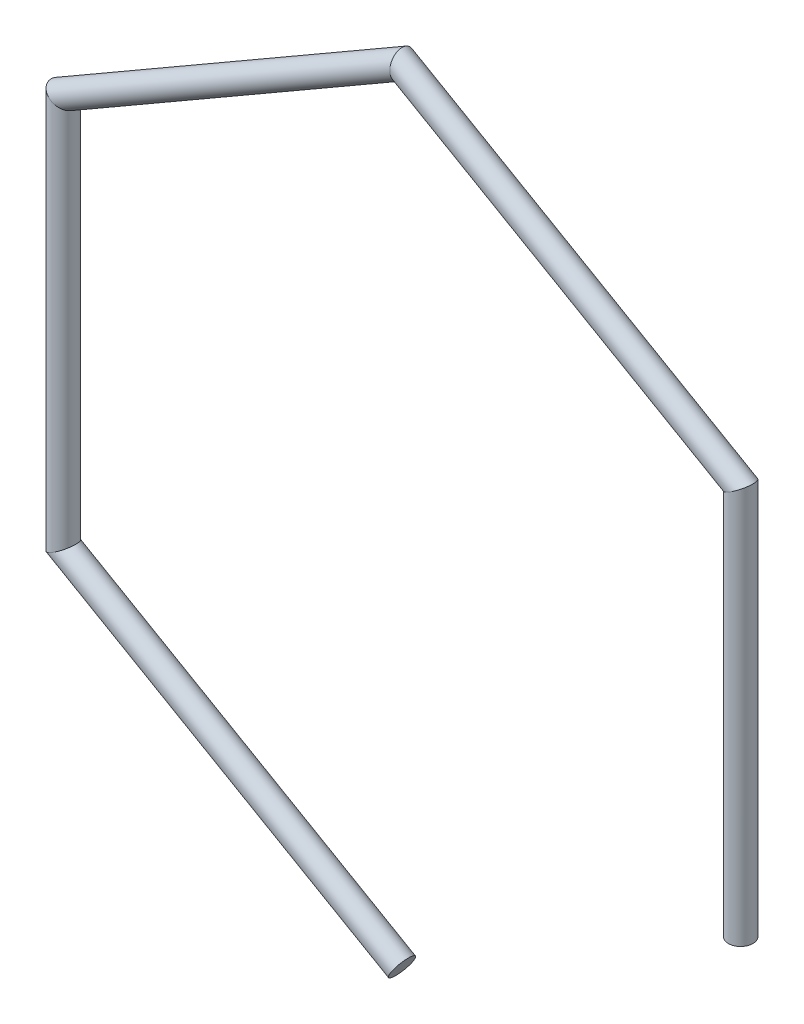
SolidWorks part; units mm, degrees
ref_plane "Front Plane" through (0, 0, 0) normal (0, 0, 1) x (1, 0, 0)
ref_plane "Top Plane" through (0, 0, 0) normal (0, 1, 0) x (1, 0, 0)
ref_plane "Right Plane" through (0, 0, 0) normal (1, 0, 0) x (0, 0, -1)
sketch "Sketch1" plane through (0, 0, 0) normal (0, 0, 1) x (1, 0, 0)
  line L0 (0, 0) -> (6.9282, -4) construction
  line L1 (0, 8) -> (-6.9282, 4)
  line L2 (-6.9282, 4) -> (-6.9282, -4)
  line L3 (-6.9282, -4) -> (0, -8)
  line L5 (6.9282, -4) -> (6.9282, 4)
  line L6 (6.9282, 4) -> (0, 8)
  line L7 (0, 0) -> (0, -8) construction
  line L9 (-19.2272, -19.1008) -> (-5.9356, -11.4269) [skipped]
  circle A0 centre (0, 0) radius 6.9282 construction
  circle A1 centre (0, 0) radius 8 construction
  point P10 (0, -28.9537)
  point P11 (0, 0)
  point P14 (26.8439, -10.1344)
  dimension "D1" = 16
ref_plane "Plane1" through (6.9282, -4, 0) normal (0, 1, 0) x (1, 0, 0)
sketch "Sketch2" plane through (6.9282, -4, 0) normal (0, 1, 0) x (1, 0, 0)
  line L0 (-14.9282, 0) -> (1.0718, 0) construction
  line L1 (-13.8564, 0) -> (0, 0) construction
  circle A0 centre (0, 0) radius 0.25
  point P6 (-0.9127, 0)
  dimension "D1" = 0.5
sweep "Sweep1" add profiles "Sketch2" path "Sketch1"
